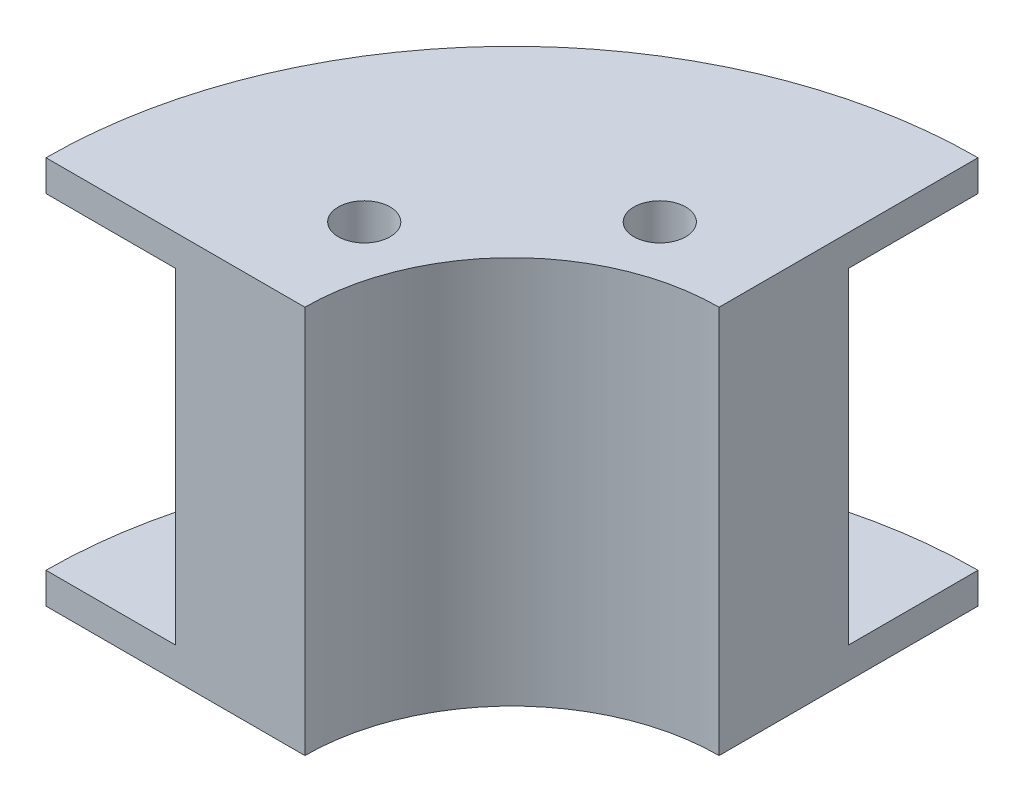
SolidWorks part; units mm, degrees
ref_plane "前视基准面" through (0, 0, 0) normal (0, 0, 1) x (1, 0, 0)
ref_plane "上视基准面" through (0, 0, 0) normal (0, 1, 0) x (1, 0, 0)
ref_plane "右视基准面" through (0, 0, 0) normal (1, 0, 0) x (0, 0, -1)
sketch "草图1" plane through (0, 0, 0) normal (0, 0, 1) x (1, 0, 0)
  line L0 (0, 39.7232) -> (0, -42.7555) construction
  line L1 (-5, 7.5) -> (5, 7.5)
  line L2 (5, 7.5) -> (5, -7.5)
  line L3 (-5, -6.3) -> (-5, -7.5)
  line L4 (0, -6.3) -> (0, 6.3)
  line L5 (0, 6.3) -> (-5, 6.3)
  line L6 (-5, 6.3) -> (-5, 7.5)
  line L7 (0, -6.3) -> (-5, -6.3)
  line L8 (-13.7302, 0) -> (22.4128, 0) construction
  line L9 (-5, -7.5) -> (5, -7.5)
  line L10 (13, 23.4038) -> (13, -22.7044) construction
  point P14 (0, 0)
  point P15 (5, 0)
  dimension "D1" = 5
  dimension "D2" = 10
  dimension "D3" = 1.2
  dimension "D4" = 15
  dimension "D5" = 13
revolve "旋转1" add sketch "草图1" angle 90 about L10
sketch "草图2" plane through (0, -7.5, 0) normal (0, -1, 0) x (1, 0, 0)
  line L0 (-5, 0) -> (5, 0) construction
  line L1 (13, -18) -> (13, -8) construction
  circle A0 centre (3.2918, -4) radius 1
  circle A1 centre (9, -9.7082) radius 1
  arc A2 (2.5, 0) -> (13, -10.5) centre (13, 0) ccw
  arc A3 (2.5, 0) -> (13, -10.5) centre (13, 0) ccw construction
  dimension "D2" = 2
  dimension "D3" = 2
  dimension "D4" = 4
  dimension "D5" = 4
  dimension "D1" = 2.5
extrude "切除-拉伸1" cut sketch "草图2" against normal through all
